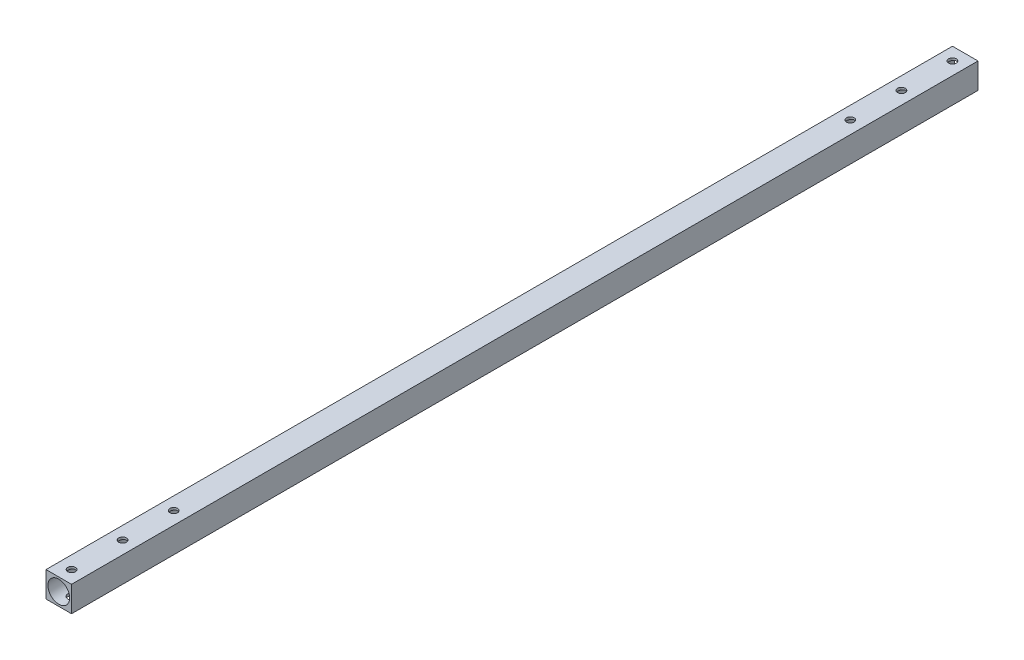
SolidWorks part; units mm, degrees
material "Thornel VCB-20 Carbon Cloth"
ref_plane "Front Plane" through (0, 0, 0) normal (0, 0, 1) x (1, 0, 0)
ref_plane "Top Plane" through (0, 0, 0) normal (0, 1, 0) x (1, 0, 0)
ref_plane "Right Plane" through (0, 0, 0) normal (1, 0, 0) x (0, 0, -1)
sketch "Sketch1" plane through (0, 0, 0) normal (0, 0, 1) x (1, 0, 0)
  line L1 (-5, -5) -> (5, -5)
  line L2 (-5, -5) -> (-5, 5)
  line L3 (-5, 5) -> (5, 5)
  line L4 (5, -5) -> (5, 5)
  line L5 (-5, -5) -> (5, 5) construction
  line L6 (-5, 5) -> (5, -5) construction
  circle A0 centre (0, 0) radius 4.25
  point P0 (0, 0)
  dimension "D3" = 8.5
  dimension "D1" = 10
  dimension "D2" = 10
extrude "Boss-Extrude1" add sketch "Sketch1" along normal blind 355
sketch "Sketch2" plane through (0, 5, 0) normal (0, 1, 0) x (1, 0, 0)
  line L0 (0, 0) -> (0, -5) construction
  line L1 (0, -5) -> (0, -25) construction
  line L2 (0, -25) -> (0, -45) construction
  line L3 (0, -355) -> (0, -350) construction
  line L4 (5, -355) -> (-5, -355) construction
  line L5 (0, -350) -> (0, -330) construction
  line L6 (0, -330) -> (0, -310) construction
  circle A0 centre (0, -5) radius 1.5
  circle A1 centre (0, -25) radius 1.5
  circle A2 centre (0, -45) radius 1.5
  circle A3 centre (0, -350) radius 1.5
  circle A4 centre (0, -330) radius 1.5
  circle A5 centre (0, -310) radius 1.5
  dimension "D3" = 3
  dimension "D4" = 5
  dimension "D6" = 3
  dimension "D1" = 5
  dimension "D2" = 20
  dimension "D5" = 20
extrude "Cut-Extrude1" cut sketch "Sketch2" against normal through all
